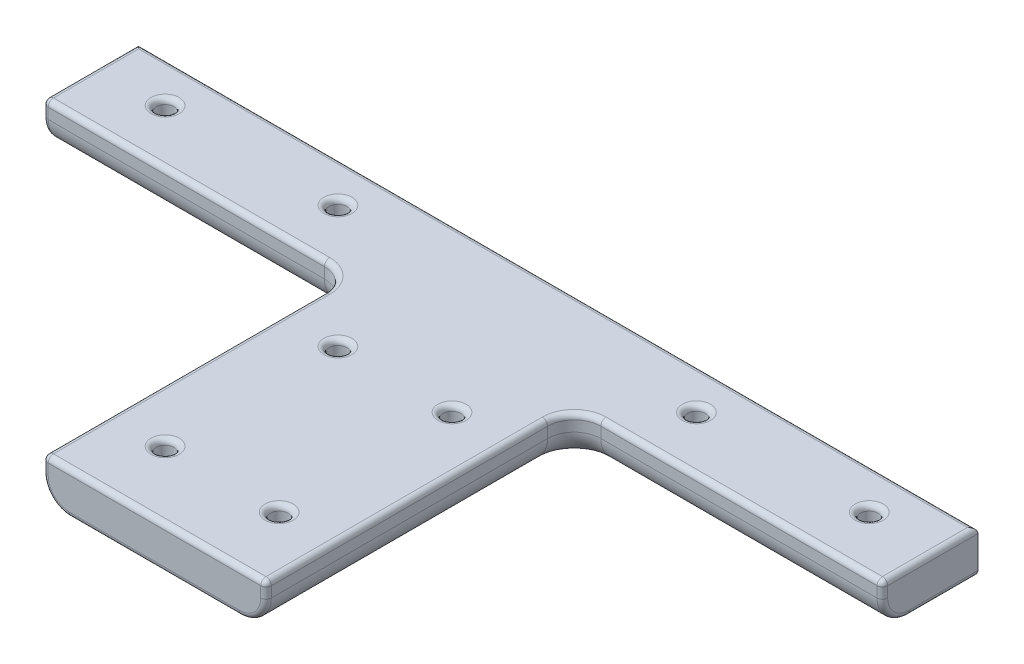
SolidWorks part; units mm, degrees
ref_plane "Front Plane" through (0, 0, 0) normal (0, 0, 1) x (1, 0, 0)
ref_plane "Top Plane" through (0, 0, 0) normal (0, 1, 0) x (1, 0, 0)
ref_plane "Right Plane" through (0, 0, 0) normal (1, 0, 0) x (0, 0, -1)
sketch "Sketch1" plane through (0, 0, 0) normal (0, 1, 0) x (1, 0, 0)
  line L1 (-79, 29) -> (-21, 29) construction
  line L2 (-79, 29) -> (-79, -29) construction
  line L3 (-79, -29) -> (-21, -29) construction
  line L4 (-21, 29) -> (-21, -29) construction
  line L5 (-79, 29) -> (-21, -29) construction
  line L6 (-79, -29) -> (-21, 29) construction
  circle A2 centre (-50, 0) radius 42.5 construction
  circle A3 centre (50, 0) radius 42.5 construction
  circle A4 centre (50, 0) radius 49 construction
  circle A5 centre (-50, 0) radius 49 construction
  circle A6 centre (-50, 0) radius 29 construction
  point P12 (49, 0)
  point P13 (55.9318, 0)
  point P14 (-53.9983, 0)
  dimension "D1" = 85
  dimension "D2" = 58
  dimension "D3" = 29
  dimension "D4" = 98
  dimension "D5" = 50
  dimension "D6" = 50
sketch "Sketch2" plane through (0, 0, 0) normal (0, 1, 0) x (1, 0, 0)
  line L4 (-21, -29) -> (21, -29)
  line L5 (-79, 29) -> (-79, 47)
  line L6 (-21, -29) -> (-21, 29)
  line L7 (-21, 29) -> (-79, 29)
  line L8 (-79, 47) -> (79, 47)
  line L9 (0, -53.9) -> (0, 53.9) construction
  line L10 (79, 29) -> (79, 47)
  line L11 (21, 29) -> (79, 29)
  line L12 (21, -29) -> (21, 29)
  point P13 (0, 47)
  point P16 (0, -29)
  dimension "D2" = 18
extrude "Boss-Extrude1" add sketch "Sketch2" against normal blind 8
sketch "Sketch6" plane through (0, 0, 0) normal (0, 1, 0) x (1, 0, 0)
  line L0 (0, 0) -> (-50, 0) construction
  line L1 (0, 0) -> (50, 0) construction
  line L5 (0, -4.4) -> (0, 4.4) construction
  circle A0 centre (-10.7351, -16.264) radius 1.65
  circle A2 centre (-50, 0) radius 42.5 construction
  circle A3 centre (-65.0626, -38.3499) radius 1.65 [skipped]
  circle A4 centre (-87.4338, -15.8606) radius 1.65 [skipped]
  circle A5 centre (-87.4338, 15.8606) radius 1.65 [skipped]
  circle A6 centre (-65.0626, 38.3499) radius 1.65 [skipped]
  circle A8 centre (-10.7351, 16.264) radius 1.65
  circle A10 centre (10.7351, 16.264) radius 1.65
  circle A11 centre (10.7351, -16.264) radius 1.65
  circle A13 centre (-33.3417, -38.5167) radius 1.65 [skipped]
  circle A14 centre (-33.3417, 38.5167) radius 1.65 [skipped]
  circle A15 centre (-33.736, 39.2649) radius 1.65
  circle A16 centre (-66.264, 39.2649) radius 1.65
  circle A17 centre (66.264, 39.2649) radius 1.65
  circle A18 centre (33.736, 39.2649) radius 1.65
  dimension "D1" = 3.3
  dimension "D2" = 22.5
  dimension "D4" = 42.5
  dimension "D5" = 22.5
  dimension "D6" = 45
  dimension "D7" = 45
  dimension "D3" = 8
extrude "Cut-Extrude1" cut sketch "Sketch6" against normal up to surface (8 mm away) up to face at (0, -8, -19)
fillet "Fillet1" radius 5 2 edges at (21, -4, -29) (-21, -4, -29)
fillet "Fillet3" radius 5 6 edges at (52.5, -8, -29) (22.4645, -8, -27.5355) (-52.5, -8, -29) (-22.4645, -8, -27.5355) (21, -8, 2.5) (-21, -8, 2.5)
fillet "Fillet4" radius 1 38 edges at (-79, -1.5, -29) (-79, -6.5355, -30.4645) (-21, -1.5, 29) (-19.5355, -6.5355, 29) (21, -1.5, 29) (19.5355, -6.5355, 29) (79, -1.5, -29) (79, -6.5355, -30.4645) (-79, 0, -38) (0, 0, -47) (79, 0, -38) (52.5, 0, -29) (22.4645, 0, -27.5355) (21, 0, 2.5) (0, 0, 29) (-21, 0, 2.5) (-22.4645, 0, -27.5355) (-52.5, 0, -29) (-10.7351, 0, 17.914) (10.7351, 0, 14.614) (10.7351, 0, -17.914) (33.736, 0, -40.9149) (66.264, 0, -40.9149) (-10.7351, 0, -14.614) (-66.264, 0, -37.6149) (-33.736, 0, -37.6149) (0, -8, -47) (-79, -8, -40.5) (0, -8, 29) (79, -8, -40.5) (-10.7351, -8, 17.914) (10.7351, -8, 17.914) (10.7351, -8, -14.614) (33.736, -8, -37.6149) (66.264, -8, -37.6149) (-10.7351, -8, -14.614) (-66.264, -8, -37.6149) (-33.736, -8, -37.6149)
